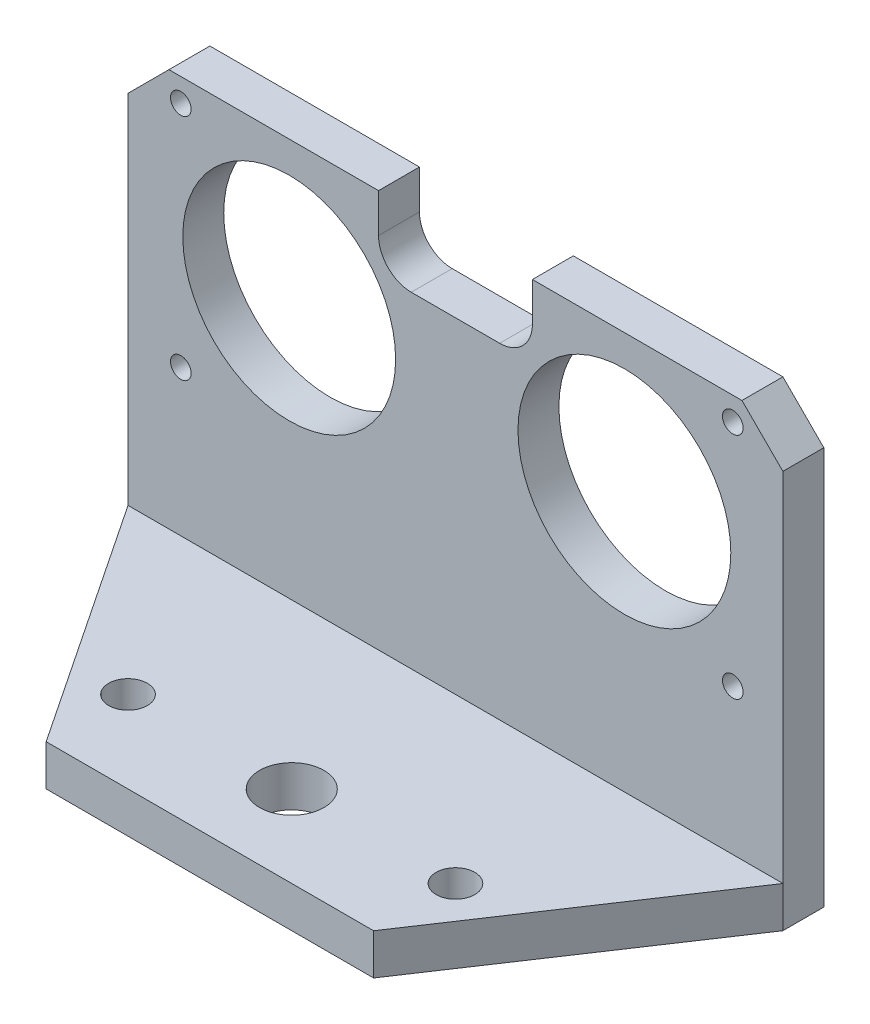
SolidWorks part; units mm, degrees
ref_plane "Front Plane" through (0, 0, 0) normal (0, 0, 1) x (1, 0, 0)
ref_plane "Top Plane" through (0, 0, 0) normal (0, 1, 0) x (1, 0, 0)
ref_plane "Right Plane" through (0, 0, 0) normal (1, 0, 0) x (0, 0, -1)
sketch "Sketch1" plane through (0, 0, 0) normal (0, 0, 1) x (1, 0, 0)
  line L1 (-25.4, 17.018) -> (25.4, 17.018)
  line L2 (-25.4, 17.018) -> (-25.4, -17.018)
  line L3 (-25.4, -17.018) -> (25.4, -17.018)
  line L4 (25.4, 17.018) -> (25.4, -17.018)
  line L5 (-25.4, 17.018) -> (25.4, -17.018) construction
  line L6 (-25.4, -17.018) -> (25.4, 17.018) construction
  point P0 (0, 0)
  dimension "D1" = 50.8
  dimension "D2" = 34.036
extrude "Boss-Extrude1" add sketch "Sketch1" along normal mid plane 3.175
sketch "Sketch2" plane through (0, 0, 1.5875) normal (0, 0, 1) x (1, 0, 0)
  line L0 (25.4, -17.018) -> (25.4, 17.018) construction
  line L1 (-25.4, -17.018) -> (25.4, -17.018)
  line L2 (-25.4, -17.018) -> (-25.4, -13.843)
  line L3 (-25.4, -13.843) -> (25.4, -13.843)
  line L4 (25.4, -17.018) -> (25.4, -13.843)
  dimension "D1" = 3.175
extrude "Boss-Extrude2" add sketch "Sketch2" along normal blind 19.05
chamfer "Chamfer1" distance 12.7 angle 45 2 edges at (-25.4, -15.4305, 20.6375) (25.4, -15.4305, 20.6375)
hole_wizard "Ø3.0mm Dowel Hole1" positions "Sketch4" profile "Sketch3" hole size "Ø3.0" standard "ANSI Metric"
sketch "Sketch4" plane through (0, -13.843, 0) normal (0, 1, 0) x (1, 0, 0)
  line L0 (12.7, -20.6375) -> (-12.7, -20.6375) construction
  line L1 (-25.4, -7.9375) -> (-25.4, -1.5875) construction
  line L2 (25.4, -7.9375) -> (25.4, -1.5875) construction
  point P0 (-12.7, -14.2875)
  point P2 (12.7, -14.2875)
  dimension "D1" = 6.35
  dimension "D2" = 12.7
  dimension "D3" = 12.7
sketch "Sketch3" plane through (-12.7, -13.843, 14.2875) normal (1, 0, 0) x (0, 0, 1)
  line L0 (0, 0) -> (0, 4.0753)
  line L1 (0, 4.0753) -> (1.5, 3.174)
  line L2 (1.5, 3.174) -> (1.5, 0)
  line L5 (1.5, 0) -> (0, 0)
  line L10 (0, 4.0753) -> (-1.5, 3.174) construction
  line L11 (0, -6.35) -> (0, 107.95) construction
  dimension "Hole Dia." = 3
  dimension "Hole Depth" = 3.174
  dimension "Drill Angle" = 118
chamfer "Chamfer2" distance 3.175 angle 45 2 edges at (25.4, 17.018, 0) (-25.4, 17.018, 0)
sketch "Sketch5" plane through (0, 0, -1.5875) normal (0, 0, -1) x (-1, 0, 0)
  line L0 (-5.969, 14.0011) -> (-5.969, 17.018)
  line L1 (-22.225, 17.018) -> (22.225, 17.018) construction
  line L2 (5.969, 14.0011) -> (5.969, 17.018)
  line L3 (-3.429, 11.4611) -> (3.429, 11.4611)
  line L4 (-25.4, -17.018) -> (-25.4, 13.843) construction
  line L5 (-5.969, 17.018) -> (5.969, 17.018)
  arc A0 (5.969, 14.0011) -> (3.429, 11.4611) centre (3.429, 14.0011) cw
  arc A1 (-3.429, 11.4611) -> (-5.969, 14.0011) centre (-3.429, 14.0011) cw
  dimension "D2" = 2.54
  dimension "D4" = 19.431
  dimension "D1" = 11.938
  dimension "D3" = 5.5569
extrude "Cut-Extrude1" cut sketch "Sketch5" against normal up to surface (3.175 mm away) up to face at (4.2333, 5.6727, 1.5875)
sketch "Sketch7" plane through (0, 0, -1.5875) normal (0, 0, -1) x (-1, 0, 0)
  circle A0 centre (12.896, 6.34) radius 8.255
  dimension "D1" = 16.51
extrude "Cut-Extrude3" cut sketch "Sketch7" against normal up to surface (3.175 mm away) up to face at (2.1167, 9.8287, 1.5875)
sketch "Sketch8" plane through (0, 0, -1.5875) normal (0, 0, -1) x (-1, 0, 0)
  circle A0 centre (-13.104, 6.34) radius 8.255
  dimension "D1" = 16.51
extrude "Cut-Extrude4" cut sketch "Sketch8" against normal up to surface (3.175 mm away) up to face at (-4.641, 6.34, 1.5875)
sketch "Sketch9" plane through (0, 0, 1.5875) normal (0, 0, 1) x (1, 0, 0)
  circle A0 centre (-21.306, 15.21) radius 0.8
  circle A1 centre (21.514, 15.21) radius 0.8
  circle A2 centre (21.514, -2.53) radius 0.8
  circle A3 centre (-21.306, -2.53) radius 0.8
extrude "Cut-Extrude5" cut sketch "Sketch9" against normal up to surface (3.175 mm away) up to face at (4.849, 6.34, -1.5875)
sketch "Sketch11" plane through (0, -13.843, 0) normal (0, 1, 0) x (1, 0, 0)
  line L0 (-12.7, -20.6375) -> (-25.4, -1.5875)
  line L1 (-25.4, -1.5875) -> (-25.4, -7.9375)
  line L2 (-25.4, -7.9375) -> (-12.7, -20.6375)
  line L3 (25.4, -1.5875) -> (12.7, -20.6375)
  line L4 (12.7, -20.6375) -> (25.4, -7.9375)
  line L5 (25.4, -7.9375) -> (25.4, -1.5875)
extrude "Cut-Extrude6" cut sketch "Sketch11" against normal up to surface (3.175 mm away) up to face at (-12.7, -17.018, 15.7875)
sketch "Sketch13" plane through (0, -13.843, 0) normal (0, 1, 0) x (1, 0, 0)
  circle A0 centre (0, -14.2875) radius 2.5
  circle A1 centre (-12.7, -14.2875) radius 1.5 construction
  circle A2 centre (-12.7, -14.2875) radius 1.5
  circle A3 centre (12.7, -14.2875) radius 1.5 construction
  circle A4 centre (12.7, -14.2875) radius 1.5
  point P2 (0, 0)
  dimension "D1" = 5
extrude "Cut-Extrude7" cut sketch "Sketch13" against normal through all
